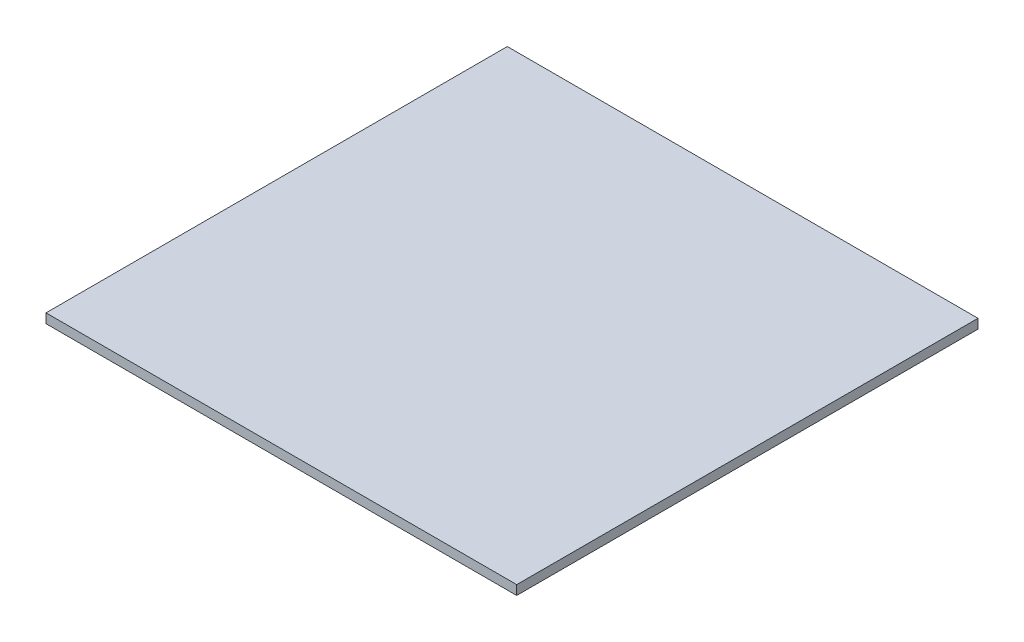
SolidWorks part; units mm, degrees
ref_plane "Front Plane" through (0, 0, 0) normal (0, 0, 1) x (1, 0, 0)
ref_plane "Top Plane" through (0, 0, 0) normal (0, 1, 0) x (1, 0, 0)
ref_plane "Right Plane" through (0, 0, 0) normal (1, 0, 0) x (0, 0, -1)
sketch "Sketch1" plane through (0, 0, 0) normal (0, 1, 0) x (1, 0, 0)
  line L1 (-317.5, -311.15) -> (317.5, -311.15)
  line L2 (-317.5, -311.15) -> (-317.5, 311.15)
  line L3 (-317.5, 311.15) -> (317.5, 311.15)
  line L4 (317.5, -311.15) -> (317.5, 311.15)
  line L5 (-317.5, -311.15) -> (317.5, 311.15) construction
  line L6 (-317.5, 311.15) -> (317.5, -311.15) construction
  point P0 (0, 0)
  dimension "D1" = 635
  dimension "D2" = 622.3
extrude "Boss-Extrude1" add sketch "Sketch1" along normal blind 12.7
